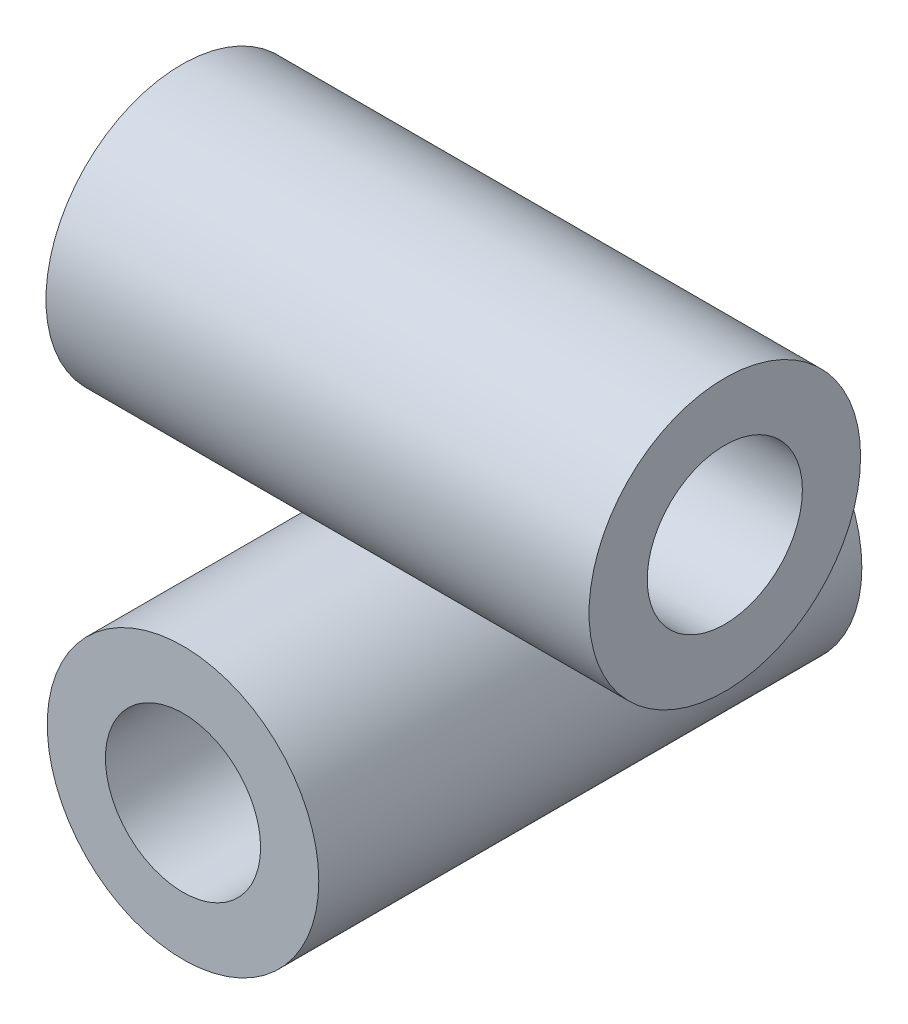
SolidWorks part; units mm, degrees
ref_plane "Front Plane" through (0, 0, 0) normal (1, 0, 0) x (0, 1, 0)
ref_plane "Top Plane" through (0, 0, 0) normal (0, 0, 1) x (0, 1, 0)
ref_plane "Right Plane" through (0, 0, 0) normal (0, 1, 0) x (-1, 0, 0)
sketch "Sketch2" plane through (0, 0, 0) normal (0, 0, 1) x (0, 1, 0)
  circle A0 centre (0, 0) radius 14
  circle A1 centre (0, 0) radius 8
  dimension "D1" = 28
  dimension "D2" = 16
extrude "Boss-Extrude1" add sketch "Sketch2" along normal blind 56
sketch "Sketch4" plane through (0, 0, 0) normal (1, 0, 0) x (0, 1, 0)
  circle A0 centre (24, 28.1327) radius 14
  circle A1 centre (24, 28.1327) radius 8
  dimension "D1" = 28
  dimension "D2" = 16
  dimension "D3" = 24
extrude "Boss-Extrude2" add sketch "Sketch4" along normal mid plane 56
